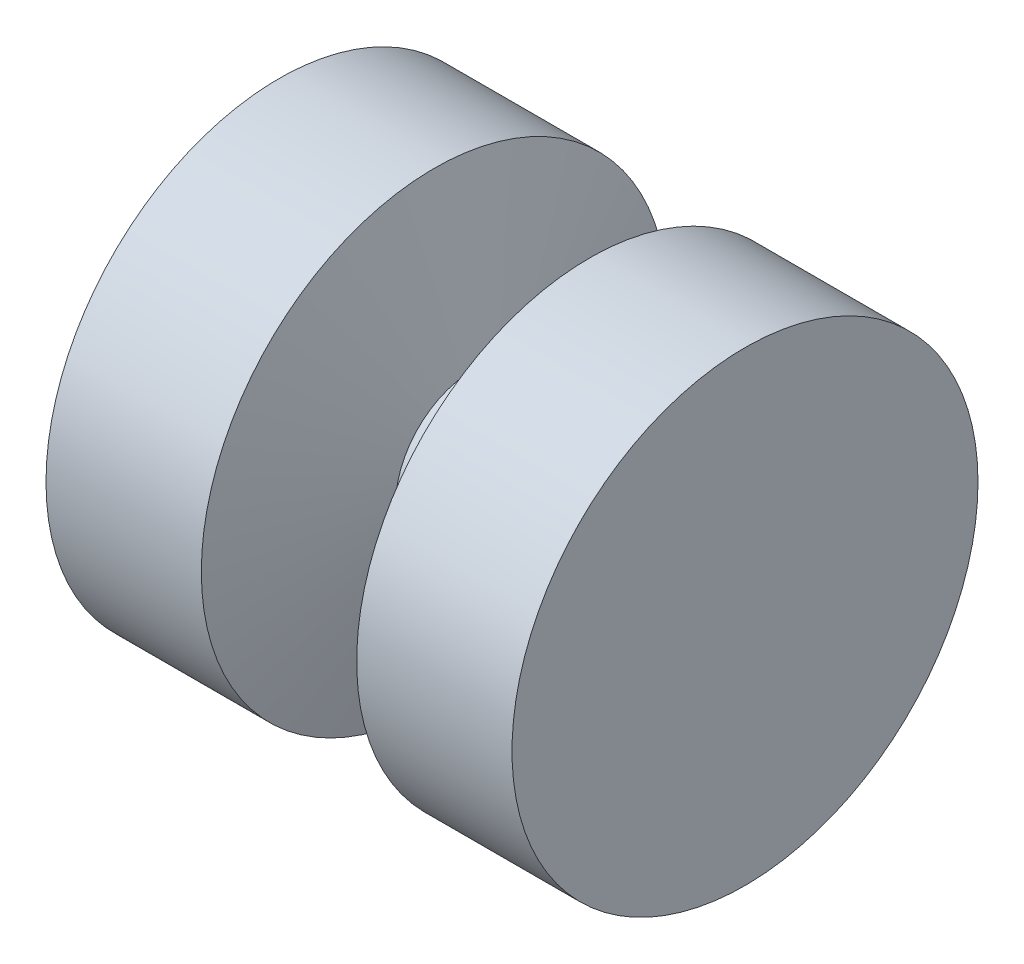
SolidWorks part; units mm, degrees
ref_plane "Front Plane" through (0, 0, 0) normal (0, 0, 1) x (1, 0, 0)
ref_plane "Top Plane" through (0, 0, 0) normal (0, 1, 0) x (1, 0, 0)
ref_plane "Right Plane" through (0, 0, 0) normal (1, 0, 0) x (0, 0, -1)
sketch "Sketch1" plane through (0, 0, 0) normal (1, 0, 0) x (0, 0, -1)
  circle A0 centre (0, 0) radius 15
  dimension "D1" = 30
extrude "Boss-Extrude1" add sketch "Sketch1" along normal mid plane 30
sketch "Sketch2" plane through (0, 0, 0) normal (0, 0, 1) x (1, 0, 0)
  line L0 (15, 15) -> (-15, 15) construction
  line L1 (15, 15) -> (5, 15)
  line L2 (-15, -15) -> (15, -15) construction
  line L3 (-15, 15) -> (-15, -15) construction
  line L4 (15, -15) -> (15, 15) construction
  line L5 (-15, -15) -> (15, -15)
  line L6 (-15, 15) -> (-15, -15)
  line L7 (15, -15) -> (15, 15)
  line L8 (5, 15) -> (2.5, 5)
  line L9 (2.5, 5) -> (-2.5, 5)
  line L10 (-2.5, 5) -> (-5, 15)
  line L11 (0, 0) -> (15, 0) construction
  line L12 (-5, 15) -> (-15, 15)
  line L13 (-5, 15) -> (5, 15)
  point P11 (-2.5, 5)
  point P12 (2.5, 5)
  point P13 (0, 0)
  dimension "D1" = 5
  dimension "D2" = 5
  dimension "D3" = 10
revolve "Cut-Revolve1" cut sketch "Sketch2" angle 360 about L11
